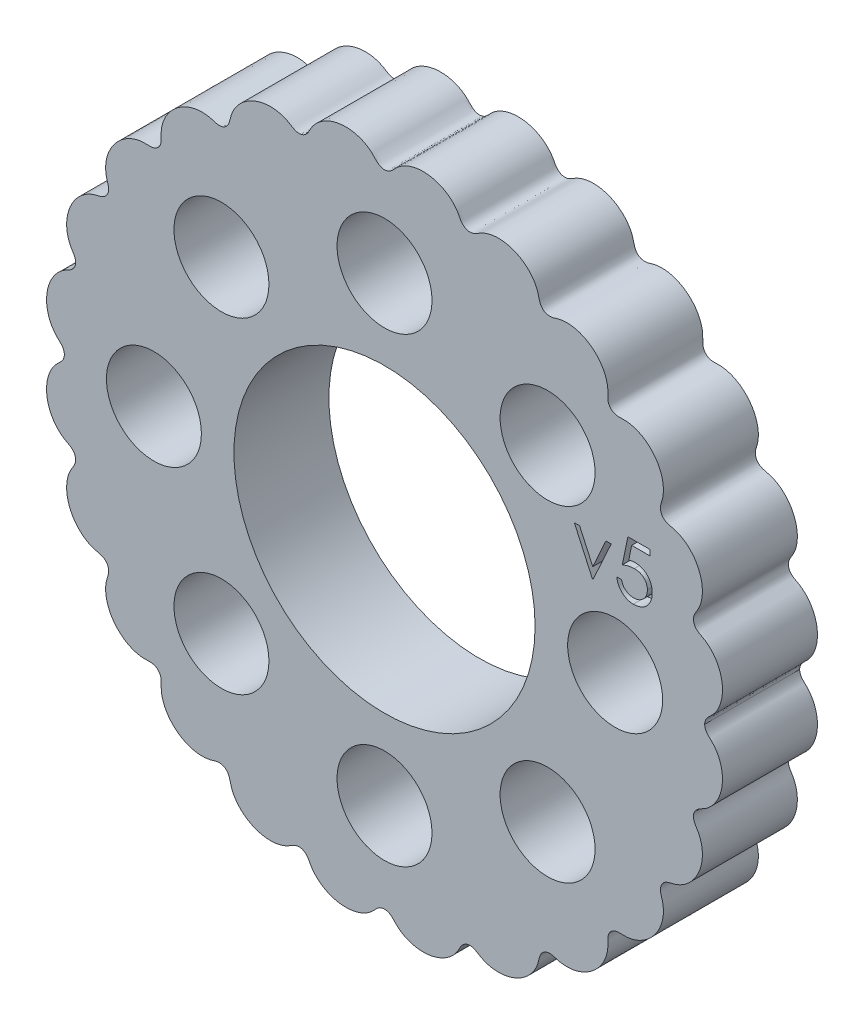
SolidWorks part; units mm, degrees
ref_plane "Plan de face" through (0, 0, 0) normal (0, 0, 1) x (1, 0, 0)
ref_plane "Plan de dessus" through (0, 0, 0) normal (0, 1, 0) x (1, 0, 0)
ref_plane "Plan de droite" through (0, 0, 0) normal (1, 0, 0) x (0, 0, -1)
sketch "Esquisse1" plane through (0, 0, 0) normal (0, 0, 1) x (1, 0, 0)
  line L0 (-1000, 0) -> (49000, 0) construction
  spline S0 degree 4 poles (22.9955, 6.6042) (22.9643, 6.5397) (22.914, 6.4032) (22.9023, 6.1862) (23.0214, 5.9244) (23.2219, 5.7605) (23.4288, 5.659) (23.6594, 5.5306) (23.9059, 5.3649) (24.1666, 5.1353) (24.4254, 4.835) (24.6422, 4.5029) (24.8162, 4.1468) (24.946, 3.7722) (25.0308, 3.385) (25.0698, 2.9906) (25.0624, 2.5943) (25.0079, 2.2017) (24.9068, 1.8224) (24.7781, 1.5066) (24.64, 1.2523) (24.5081, 1.0548) (24.3917, 0.9046) (24.2647, 0.7631) (24.1289, 0.6302) (24.012, 0.5251) (23.9248, 0.4355) (23.8688, 0.3622) (23.8363, 0.3122) (23.8082, 0.2597) (23.7852, 0.2044) (23.7697, 0.1547) (23.76, 0.1121) (23.7533, 0.0661) (23.7501, 0.0228) (23.7495, -0.004) (23.7513, -0.04) (23.7542, -0.0715) (23.7595, -0.1093) (23.7688, -0.1512) (23.7835, -0.1997) (23.8056, -0.2538) (23.8324, -0.3054) (23.8635, -0.3546) (23.9194, -0.4297) (24.009, -0.5227) (24.1313, -0.6322) (24.2737, -0.7721) (24.4392, -0.959) (24.6145, -1.2025) (24.7855, -1.5135) (24.9316, -1.8961) (25.0271, -2.299) (25.0708, -2.7153) (25.0622, -3.1311) (25.0033, -3.5401) (24.8958, -3.9363) (24.7419, -4.314) (24.5445, -4.6645) (24.307, -4.9822) (24.0331, -5.2614) (23.7654, -5.4667) (23.5164, -5.6129) (23.2956, -5.7243) (23.1195, -5.8363) (22.9763, -6.0087) (22.9044, -6.234) (22.925, -6.462) (23.0164, -6.6581) (23.1266, -6.8267) (23.2244, -6.9889) (23.3341, -7.1984) (23.4412, -7.4619) (23.5336, -7.7957) (23.5876, -8.2004) (23.5865, -8.623) (23.5267, -9.0558) (23.3808, -9.5868) (23.1436, -10.0885) (22.8209, -10.5434) (22.4327, -10.9196) (22.1006, -11.1627) (21.7948, -11.3267) (21.5321, -11.4304) (21.3065, -11.4954) (21.1232, -11.5381) (20.9306, -11.5808) (20.7385, -11.6689) (20.5325, -11.8672) (20.4495, -12.16) (20.5219, -12.4298) (20.6167, -12.7241) (20.6818, -13.0067) (20.7176, -13.3406) (20.7046, -13.7295) (20.6405, -14.1156) (20.5273, -14.4945) (20.3673, -14.8595) (20.1602, -15.2112) (19.9061, -15.5428) (19.6059, -15.8469) (19.261, -16.115) (18.8955, -16.3273) (18.5181, -16.4829) (18.1828, -16.5697) (17.9011, -16.6087) (17.6647, -16.6185) (17.4754, -16.6149) (17.2743, -16.6037) (17.0588, -16.6226) (16.851, -16.7187) (16.6918, -16.8937) (16.6141, -17.104) (16.6052, -17.3124) (16.6191, -17.5593) (16.617, -17.8481) (16.5731, -18.1826) (16.4683, -18.5594) (16.3118, -18.9239) (16.107, -19.2701) (15.8569, -19.5923) (15.5674, -19.8834) (15.2427, -20.1389) (14.8869, -20.3543) (14.5046, -20.5246) (14.1078, -20.6433) (13.7035, -20.7081) (13.2985, -20.7166) (12.9508, -20.673) (12.6603, -20.5981) (12.4161, -20.517) (12.2029, -20.4723) (11.9744, -20.5019) (11.768, -20.6211) (11.6281, -20.8042) (11.5602, -21.0112) (11.5084, -21.2632) (11.428, -21.5523) (11.2919, -21.8752) (11.082, -22.2216) (10.8237, -22.5394) (10.5226, -22.8236) (10.1839, -23.0696) (9.8195, -23.2701) (9.4358, -23.4235) (9.039, -23.5286) (8.6349, -23.5841) (8.2327, -23.5884) (7.8388, -23.5416) (7.4601, -23.444) (7.1484, -23.3148) (6.8973, -23.1723) (6.6904, -23.0367) (6.5054, -22.9402) (6.2844, -22.9024) (6.0534, -22.9528) (5.8662, -23.0846) (5.7421, -23.2618) (5.6512, -23.4416) (5.5596, -23.6073) (5.4331, -23.8072) (5.2584, -24.0316) (5.0155, -24.2786) (4.6921, -24.5276) (4.2308, -24.7924) (3.7121, -24.9769) (3.1672, -25.0695) (2.6142, -25.0665) (2.1723, -25.0046) (1.7597, -24.8871) (1.3831, -24.721) (1.0882, -24.5382) (0.867, -24.3625) (0.6979, -24.1997) (0.5693, -24.0623) (0.436, -23.9168) (0.2637, -23.7945) (-0.011, -23.7153) (-0.3061, -23.7898) (-0.5036, -23.9874) (-0.7111, -24.2166) (-0.9232, -24.4143) (-1.1945, -24.6122) (-1.5378, -24.7955) (-1.9042, -24.933) (-2.289, -25.0244) (-2.6851, -25.0684) (-3.0932, -25.0648) (-3.5074, -25.0106) (-3.9209, -24.9026) (-4.3256, -24.738) (-4.6921, -24.5276) (-5.0155, -24.2786) (-5.2584, -24.0316) (-5.4331, -23.8072) (-5.5596, -23.6073) (-5.6512, -23.4416) (-5.7421, -23.2618) (-5.8662, -23.0846) (-6.0534, -22.9528) (-6.2844, -22.9024) (-6.5054, -22.9402) (-6.6904, -23.0367) (-6.8973, -23.1723) (-7.1484, -23.3148) (-7.4601, -23.444) (-7.8388, -23.5416) (-8.2327, -23.5884) (-8.6349, -23.5841) (-9.039, -23.5286) (-9.4358, -23.4235) (-9.8195, -23.2701) (-10.1839, -23.0696) (-10.5226, -22.8236) (-10.8237, -22.5394) (-11.082, -22.2216) (-11.2919, -21.8752) (-11.428, -21.5523) (-11.5084, -21.2632) (-11.5602, -21.0112) (-11.6281, -20.8042) (-11.768, -20.6211) (-11.9744, -20.5019) (-12.2029, -20.4723) (-12.4161, -20.517) (-12.6603, -20.5981) (-12.9508, -20.673) (-13.2985, -20.7166) (-13.7035, -20.7081) (-14.1078, -20.6433) (-14.6048, -20.4946) (-15.1642, -20.2163) (-15.6552, -19.8308) (-16.055, -19.3579) (-16.3118, -18.9239) (-16.4683, -18.5594) (-16.5731, -18.1826) (-16.617, -17.8481) (-16.6191, -17.5593) (-16.6052, -17.3124) (-16.6141, -17.104) (-16.6918, -16.8937) (-16.851, -16.7187) (-17.0588, -16.6226) (-17.2743, -16.6037) (-17.4754, -16.6149) (-17.6647, -16.6185) (-17.9011, -16.6087) (-18.1828, -16.5697) (-18.5181, -16.4829) (-18.8955, -16.3273) (-19.261, -16.1151) (-19.6059, -15.8469) (-19.9061, -15.5428) (-20.1602, -15.2112) (-20.3673, -14.8595) (-20.5273, -14.4945) (-20.6405, -14.1156) (-20.7046, -13.7294) (-20.7175, -13.3407) (-20.6818, -13.0066) (-20.6166, -12.7243) (-20.522, -12.4295) (-20.4494, -12.1605) (-20.5243, -11.8962) (-20.683, -11.7227) (-20.8176, -11.632) (-20.958, -11.5755) (-21.1234, -11.5373) (-21.3064, -11.4958) (-21.5321, -11.4302) (-21.7948, -11.3268) (-22.1006, -11.1626) (-22.4327, -10.9196) (-22.7408, -10.6211) (-23.0153, -10.2693) (-23.2393, -9.8862) (-23.4104, -9.4792) (-23.5267, -9.0558) (-23.5865, -8.623) (-23.5876, -8.2004) (-23.5336, -7.7957) (-23.4412, -7.4619) (-23.3341, -7.1984) (-23.2244, -6.9889) (-23.1266, -6.8267) (-23.0164, -6.6581) (-22.925, -6.462) (-22.9044, -6.234) (-22.9763, -6.0087) (-23.1195, -5.8363) (-23.2956, -5.7243) (-23.5164, -5.6129) (-23.7654, -5.4667) (-24.0331, -5.2614) (-24.307, -4.9822) (-24.5445, -4.6645) (-24.7419, -4.314) (-24.8958, -3.9363) (-25.0033, -3.5401) (-25.0622, -3.1311) (-25.0708, -2.7153) (-25.0271, -2.299) (-24.9316, -1.8961) (-24.7855, -1.5135) (-24.6145, -1.2025) (-24.4393, -0.959) (-24.2737, -0.7721) (-24.1313, -0.6321) (-23.9982, -0.5131) (-23.8995, -0.4084) (-23.8391, -0.3182) (-23.8055, -0.2539) (-23.7835, -0.1997) (-23.7688, -0.1512) (-23.7595, -0.1093) (-23.7542, -0.0715) (-23.7513, -0.04) (-23.7495, -0.0037) (-23.7502, 0.0234) (-23.7534, 0.0677) (-23.7604, 0.1144) (-23.7705, 0.1578) (-23.7867, 0.2087) (-23.8107, 0.2649) (-23.8399, 0.3183) (-23.8736, 0.369) (-23.9317, 0.4432) (-24.0215, 0.5339) (-24.141, 0.6413) (-24.279, 0.7779) (-24.4075, 0.9235) (-24.5249, 1.0783) (-24.6575, 1.2816) (-24.7976, 1.5478) (-24.9275, 1.8824) (-25.0256, 2.2876) (-25.071, 2.7111) (-25.0623, 3.1368) (-25.0002, 3.5582) (-24.8859, 3.9683) (-24.7199, 4.3608) (-24.4999, 4.7349) (-24.2231, 5.0813) (-23.9331, 5.3469) (-23.6469, 5.5411) (-23.3456, 5.7009) (-23.0735, 5.8417) (-22.8982, 6.1368) (-22.9147, 6.4027) (-22.9638, 6.54) (-22.9956, 6.6042) knots 0 0 0 0 0 0.002762 0.005524 0.008057 0.010589 0.012487 0.014385 0.018181 0.021977 0.025773 0.029569 0.033366 0.037162 0.040959 0.044755 0.048552 0.052348 0.056144 0.059791 0.061614 0.063437 0.06526 0.067083 0.068906 0.070729 0.071301 0.071873 0.072445 0.073016 0.073588 0.07416 0.074446 0.074731 0.075303 0.075582 0.075861 0.07614 0.076419 0.076977 0.077535 0.078093 0.078652 0.07921 0.079768 0.081683 0.083599 0.085515 0.08743 0.091261 0.095093 0.099101 0.103109 0.107118 0.111126 0.115032 0.118938 0.122843 0.126749 0.130438 0.134127 0.137815 0.13966 0.141504 0.143638 0.145771 0.148068 0.150364 0.15218 0.153996 0.155812 0.157628 0.16126 0.164892 0.169075 0.173257 0.177439 0.181621 0.190162 0.194433 0.198704 0.20231 0.205917 0.20772 0.209523 0.211327 0.21313 0.215313 0.217496 0.222107 0.223949 0.225791 0.229476 0.23316 0.236844 0.240662 0.24448 0.248298 0.252116 0.256299 0.260481 0.264663 0.268845 0.272477 0.276109 0.277925 0.279741 0.281557 0.283373 0.28567 0.287966 0.2901 0.292233 0.294078 0.295922 0.299611 0.3033 0.306988 0.310894 0.3148 0.318706 0.322612 0.32662 0.330628 0.334637 0.338645 0.342476 0.346307 0.350139 0.352054 0.35397 0.356202 0.358434 0.360667 0.362899 0.364815 0.36673 0.370561 0.374393 0.378224 0.382232 0.386241 0.390249 0.394257 0.398163 0.402069 0.405975 0.40988 0.413569 0.417258 0.420947 0.422791 0.424635 0.426769 0.428902 0.431199 0.433495 0.435311 0.437127 0.438943 0.440759 0.444392 0.448024 0.452206 0.456388 0.464752 0.469023 0.473294 0.477564 0.481835 0.485441 0.489048 0.490851 0.492655 0.494458 0.496261 0.498444 0.500627 0.505239 0.507081 0.508923 0.512607 0.516291 0.519975 0.523793 0.527611 0.53143 0.535248 0.53943 0.543612 0.547794 0.551976 0.555609 0.559241 0.561057 0.562873 0.564689 0.566505 0.568801 0.571098 0.573231 0.575365 0.577209 0.579053 0.582742 0.586431 0.59012 0.594025 0.597931 0.601837 0.605743 0.609751 0.61376 0.617768 0.621776 0.625607 0.629439 0.63327 0.635186 0.637101 0.639333 0.641566 0.643798 0.64603 0.647946 0.649861 0.653693 0.657524 0.661355 0.665364 0.669372 0.677388 0.6852 0.689106 0.693012 0.6967 0.700389 0.704078 0.705922 0.707767 0.7099 0.712034 0.71433 0.716627 0.718443 0.720259 0.722075 0.723891 0.727523 0.731155 0.735337 0.739519 0.743701 0.747884 0.751702 0.75552 0.759338 0.763156 0.76684 0.770525 0.774209 0.776051 0.777893 0.782504 0.784687 0.785779 0.78687 0.788673 0.790477 0.79228 0.794083 0.79769 0.801296 0.805567 0.809838 0.814108 0.818379 0.822561 0.826743 0.830926 0.835108 0.83874 0.842372 0.844188 0.846004 0.84782 0.849636 0.851932 0.854229 0.856362 0.858496 0.86034 0.862185 0.865873 0.869562 0.873251 0.877157 0.881063 0.884968 0.888874 0.892882 0.896891 0.900899 0.904907 0.908739 0.91257 0.914486 0.916401 0.918317 0.920232 0.921349 0.921907 0.922465 0.923023 0.923581 0.92386 0.924139 0.924418 0.924697 0.925281 0.925573 0.925865 0.926449 0.927033 0.927617 0.928201 0.928785 0.929369 0.931232 0.933095 0.934957 0.93682 0.938683 0.940546 0.944272 0.94835 0.952428 0.956506 0.960584 0.964661 0.968739 0.972817 0.976894 0.98129 0.985685 0.987883 0.99008 0.994476 0.997238 1 1 1 1 1 construction
  spline S1 degree 4 poles (23.75, 0) (23.75, -0.0062) (23.7502, -0.0186) (23.7513, -0.04) (23.7542, -0.0715) (23.7595, -0.1093) (23.7688, -0.1512) (23.7835, -0.1997) (23.8056, -0.2538) (23.8324, -0.3054) (23.8635, -0.3546) (23.9194, -0.4297) (24.009, -0.5227) (24.1313, -0.6322) (24.2737, -0.7721) (24.4392, -0.959) (24.6145, -1.2025) (24.7855, -1.5135) (24.9316, -1.8961) (25.0271, -2.299) (25.0708, -2.7153) (25.0622, -3.1311) (25.0033, -3.5401) (24.8958, -3.9363) (24.7419, -4.314) (24.5445, -4.6645) (24.307, -4.9822) (24.0331, -5.2614) (23.7654, -5.4667) (23.5164, -5.6129) (23.2956, -5.7243) (23.1195, -5.8363) (22.9763, -6.0087) (22.9044, -6.234) (22.925, -6.462) (23.0164, -6.6581) (23.1266, -6.8267) (23.2244, -6.9889) (23.3341, -7.1984) (23.4412, -7.4619) (23.5336, -7.7957) (23.5876, -8.2004) (23.5865, -8.623) (23.5267, -9.0558) (23.3808, -9.5868) (23.1436, -10.0885) (22.8209, -10.5434) (22.4327, -10.9196) (22.1006, -11.1627) (21.7948, -11.3267) (21.5321, -11.4304) (21.3065, -11.4954) (21.1232, -11.5381) (20.9306, -11.5808) (20.7385, -11.6689) (20.5325, -11.8672) (20.4495, -12.16) (20.5219, -12.4298) (20.6167, -12.7241) (20.6818, -13.0067) (20.7176, -13.3406) (20.7046, -13.7295) (20.6405, -14.1156) (20.5273, -14.4945) (20.3673, -14.8595) (20.1602, -15.2112) (19.9061, -15.5428) (19.6059, -15.8469) (19.261, -16.115) (18.8955, -16.3273) (18.5181, -16.4829) (18.1828, -16.5697) (17.9011, -16.6087) (17.6647, -16.6185) (17.4754, -16.6149) (17.2743, -16.6037) (17.0588, -16.6226) (16.851, -16.7187) (16.6918, -16.8937) (16.6141, -17.104) (16.6052, -17.3124) (16.6191, -17.5593) (16.617, -17.8481) (16.5731, -18.1826) (16.4683, -18.5594) (16.3118, -18.9239) (16.107, -19.2701) (15.8569, -19.5923) (15.5674, -19.8834) (15.2427, -20.1389) (14.8869, -20.3543) (14.5046, -20.5246) (14.1078, -20.6433) (13.7035, -20.7081) (13.2985, -20.7166) (12.9508, -20.673) (12.6603, -20.5981) (12.4161, -20.517) (12.2029, -20.4723) (11.9744, -20.5019) (11.768, -20.6211) (11.6281, -20.8042) (11.5602, -21.0112) (11.5084, -21.2632) (11.428, -21.5523) (11.2919, -21.8752) (11.082, -22.2216) (10.8237, -22.5394) (10.5226, -22.8236) (10.1839, -23.0696) (9.8195, -23.2701) (9.4358, -23.4235) (9.039, -23.5286) (8.6349, -23.5841) (8.2327, -23.5884) (7.8388, -23.5416) (7.4601, -23.444) (7.1484, -23.3148) (6.8973, -23.1723) (6.6904, -23.0367) (6.5054, -22.9402) (6.2844, -22.9024) (6.0534, -22.9528) (5.8662, -23.0846) (5.7421, -23.2618) (5.6512, -23.4416) (5.5596, -23.6073) (5.4331, -23.8072) (5.2584, -24.0316) (5.0155, -24.2786) (4.6921, -24.5276) (4.2308, -24.7924) (3.7121, -24.9769) (3.1672, -25.0695) (2.6142, -25.0665) (2.1723, -25.0046) (1.7597, -24.8871) (1.3831, -24.721) (1.0882, -24.5382) (0.867, -24.3625) (0.6979, -24.1997) (0.5693, -24.0623) (0.436, -23.9168) (0.2637, -23.7945) (-0.011, -23.7153) (-0.3061, -23.7898) (-0.5036, -23.9874) (-0.7111, -24.2166) (-0.9232, -24.4143) (-1.1945, -24.6122) (-1.5378, -24.7955) (-1.9042, -24.933) (-2.289, -25.0244) (-2.6851, -25.0684) (-3.0932, -25.0648) (-3.5074, -25.0106) (-3.9209, -24.9026) (-4.3256, -24.738) (-4.6921, -24.5276) (-5.0155, -24.2786) (-5.2584, -24.0316) (-5.4331, -23.8072) (-5.5596, -23.6073) (-5.6512, -23.4416) (-5.7421, -23.2618) (-5.8662, -23.0846) (-6.0534, -22.9528) (-6.2844, -22.9024) (-6.5054, -22.9402) (-6.6904, -23.0367) (-6.8973, -23.1723) (-7.1484, -23.3148) (-7.4601, -23.444) (-7.8388, -23.5416) (-8.2327, -23.5884) (-8.6349, -23.5841) (-9.039, -23.5286) (-9.4358, -23.4235) (-9.8195, -23.2701) (-10.1839, -23.0696) (-10.5226, -22.8236) (-10.8237, -22.5394) (-11.082, -22.2216) (-11.2919, -21.8752) (-11.428, -21.5523) (-11.5084, -21.2632) (-11.5602, -21.0112) (-11.6281, -20.8042) (-11.768, -20.6211) (-11.9744, -20.5019) (-12.2029, -20.4723) (-12.4161, -20.517) (-12.6603, -20.5981) (-12.9508, -20.673) (-13.2985, -20.7166) (-13.7035, -20.7081) (-14.1078, -20.6433) (-14.6048, -20.4946) (-15.1642, -20.2163) (-15.6552, -19.8308) (-16.055, -19.3579) (-16.3118, -18.9239) (-16.4683, -18.5594) (-16.5731, -18.1826) (-16.617, -17.8481) (-16.6191, -17.5593) (-16.6052, -17.3124) (-16.6141, -17.104) (-16.6918, -16.8937) (-16.851, -16.7187) (-17.0588, -16.6226) (-17.2743, -16.6037) (-17.4754, -16.6149) (-17.6647, -16.6185) (-17.9011, -16.6087) (-18.1828, -16.5697) (-18.5181, -16.4829) (-18.8955, -16.3273) (-19.261, -16.1151) (-19.6059, -15.8469) (-19.9061, -15.5428) (-20.1602, -15.2112) (-20.3673, -14.8595) (-20.5273, -14.4945) (-20.6405, -14.1156) (-20.7046, -13.7294) (-20.7175, -13.3407) (-20.6818, -13.0066) (-20.6166, -12.7243) (-20.522, -12.4295) (-20.4494, -12.1605) (-20.5243, -11.8962) (-20.683, -11.7227) (-20.8176, -11.632) (-20.958, -11.5755) (-21.1234, -11.5373) (-21.3064, -11.4958) (-21.5321, -11.4302) (-21.7948, -11.3268) (-22.1006, -11.1626) (-22.4327, -10.9196) (-22.7408, -10.6211) (-23.0153, -10.2693) (-23.2393, -9.8862) (-23.4104, -9.4792) (-23.5267, -9.0558) (-23.5865, -8.623) (-23.5876, -8.2004) (-23.5336, -7.7957) (-23.4412, -7.4619) (-23.3341, -7.1984) (-23.2244, -6.9889) (-23.1266, -6.8267) (-23.0164, -6.6581) (-22.925, -6.462) (-22.9044, -6.234) (-22.9763, -6.0087) (-23.1195, -5.8363) (-23.2956, -5.7243) (-23.5164, -5.6129) (-23.7654, -5.4667) (-24.0331, -5.2614) (-24.307, -4.9822) (-24.5445, -4.6645) (-24.7419, -4.314) (-24.8958, -3.9363) (-25.0033, -3.5401) (-25.0622, -3.1311) (-25.0708, -2.7153) (-25.0271, -2.299) (-24.9316, -1.8961) (-24.7855, -1.5135) (-24.6145, -1.2025) (-24.4393, -0.959) (-24.2737, -0.7721) (-24.1313, -0.6321) (-23.9982, -0.5131) (-23.8995, -0.4084) (-23.8391, -0.3182) (-23.8055, -0.2539) (-23.7835, -0.1997) (-23.7688, -0.1512) (-23.7595, -0.1093) (-23.7542, -0.0715) (-23.7513, -0.04) (-23.7502, -0.0186) (-23.75, -0.0062) (-23.75, 0) knots 0.075303 0.075303 0.075303 0.075303 0.075303 0.075582 0.075861 0.07614 0.076419 0.076977 0.077535 0.078093 0.078652 0.07921 0.079768 0.081683 0.083599 0.085515 0.08743 0.091261 0.095093 0.099101 0.103109 0.107118 0.111126 0.115032 0.118938 0.122843 0.126749 0.130438 0.134127 0.137815 0.13966 0.141504 0.143638 0.145771 0.148068 0.150364 0.15218 0.153996 0.155812 0.157628 0.16126 0.164892 0.169075 0.173257 0.177439 0.181621 0.190162 0.194433 0.198704 0.20231 0.205917 0.20772 0.209523 0.211327 0.21313 0.215313 0.217496 0.222107 0.223949 0.225791 0.229476 0.23316 0.236844 0.240662 0.24448 0.248298 0.252116 0.256299 0.260481 0.264663 0.268845 0.272477 0.276109 0.277925 0.279741 0.281557 0.283373 0.28567 0.287966 0.2901 0.292233 0.294078 0.295922 0.299611 0.3033 0.306988 0.310894 0.3148 0.318706 0.322612 0.32662 0.330628 0.334637 0.338645 0.342476 0.346307 0.350139 0.352054 0.35397 0.356202 0.358434 0.360667 0.362899 0.364815 0.36673 0.370561 0.374393 0.378224 0.382232 0.386241 0.390249 0.394257 0.398163 0.402069 0.405975 0.40988 0.413569 0.417258 0.420947 0.422791 0.424635 0.426769 0.428902 0.431199 0.433495 0.435311 0.437127 0.438943 0.440759 0.444392 0.448024 0.452206 0.456388 0.464752 0.469023 0.473294 0.477564 0.481835 0.485441 0.489048 0.490851 0.492655 0.494458 0.496261 0.498444 0.500627 0.505239 0.507081 0.508923 0.512607 0.516291 0.519975 0.523793 0.527611 0.53143 0.535248 0.53943 0.543612 0.547794 0.551976 0.555609 0.559241 0.561057 0.562873 0.564689 0.566505 0.568801 0.571098 0.573231 0.575365 0.577209 0.579053 0.582742 0.586431 0.59012 0.594025 0.597931 0.601837 0.605743 0.609751 0.61376 0.617768 0.621776 0.625607 0.629439 0.63327 0.635186 0.637101 0.639333 0.641566 0.643798 0.64603 0.647946 0.649861 0.653693 0.657524 0.661355 0.665364 0.669372 0.677388 0.6852 0.689106 0.693012 0.6967 0.700389 0.704078 0.705922 0.707767 0.7099 0.712034 0.71433 0.716627 0.718443 0.720259 0.722075 0.723891 0.727523 0.731155 0.735337 0.739519 0.743701 0.747884 0.751702 0.75552 0.759338 0.763156 0.76684 0.770525 0.774209 0.776051 0.777893 0.782504 0.784687 0.785779 0.78687 0.788673 0.790477 0.79228 0.794083 0.79769 0.801296 0.805567 0.809838 0.814108 0.818379 0.822561 0.826743 0.830926 0.835108 0.83874 0.842372 0.844188 0.846004 0.84782 0.849636 0.851932 0.854229 0.856362 0.858496 0.86034 0.862185 0.865873 0.869562 0.873251 0.877157 0.881063 0.884968 0.888874 0.892882 0.896891 0.900899 0.904907 0.908739 0.91257 0.914486 0.916401 0.918317 0.920232 0.921349 0.921907 0.922465 0.923023 0.923581 0.92386 0.924139 0.924418 0.924697 0.924697 0.924697 0.924697 0.924697 construction
  spline S2 degree 4 poles (23.75, 0) (23.75, 0.0062) (23.7502, 0.0186) (23.7513, 0.04) (23.7542, 0.0715) (23.7595, 0.1093) (23.7688, 0.1512) (23.7835, 0.1997) (23.8056, 0.2538) (23.8324, 0.3054) (23.8635, 0.3546) (23.9194, 0.4297) (24.009, 0.5227) (24.1313, 0.6322) (24.2737, 0.7721) (24.4392, 0.959) (24.6145, 1.2025) (24.7855, 1.5135) (24.9316, 1.8961) (25.0271, 2.299) (25.0708, 2.7153) (25.0622, 3.1311) (25.0033, 3.5401) (24.8958, 3.9363) (24.7419, 4.314) (24.5445, 4.6645) (24.307, 4.9822) (24.0331, 5.2614) (23.7654, 5.4667) (23.5164, 5.6129) (23.2956, 5.7243) (23.1195, 5.8363) (22.9763, 6.0087) (22.9044, 6.234) (22.925, 6.462) (23.0164, 6.6581) (23.1266, 6.8267) (23.2244, 6.9889) (23.3341, 7.1984) (23.4412, 7.4619) (23.5336, 7.7957) (23.5876, 8.2004) (23.5865, 8.623) (23.5267, 9.0558) (23.3808, 9.5868) (23.1436, 10.0885) (22.8209, 10.5434) (22.4327, 10.9196) (22.1006, 11.1627) (21.7948, 11.3267) (21.5321, 11.4304) (21.3065, 11.4954) (21.1232, 11.5381) (20.9306, 11.5808) (20.7385, 11.6689) (20.5325, 11.8672) (20.4495, 12.16) (20.5219, 12.4298) (20.6167, 12.7241) (20.6818, 13.0067) (20.7176, 13.3406) (20.7046, 13.7295) (20.6405, 14.1156) (20.5273, 14.4945) (20.3673, 14.8595) (20.1602, 15.2112) (19.9061, 15.5428) (19.6059, 15.8469) (19.261, 16.115) (18.8955, 16.3273) (18.5181, 16.4829) (18.1828, 16.5697) (17.9011, 16.6087) (17.6647, 16.6185) (17.4754, 16.6149) (17.2743, 16.6037) (17.0588, 16.6226) (16.851, 16.7187) (16.6918, 16.8937) (16.6141, 17.104) (16.6052, 17.3124) (16.6191, 17.5593) (16.617, 17.8481) (16.5731, 18.1826) (16.4683, 18.5594) (16.3118, 18.9239) (16.107, 19.2701) (15.8569, 19.5923) (15.5674, 19.8834) (15.2427, 20.1389) (14.8869, 20.3543) (14.5046, 20.5246) (14.1078, 20.6433) (13.7035, 20.7081) (13.2985, 20.7166) (12.9508, 20.673) (12.6603, 20.5981) (12.4161, 20.517) (12.2029, 20.4723) (11.9744, 20.5019) (11.768, 20.6211) (11.6281, 20.8042) (11.5602, 21.0112) (11.5084, 21.2632) (11.428, 21.5523) (11.2919, 21.8752) (11.082, 22.2216) (10.8237, 22.5394) (10.5226, 22.8236) (10.1839, 23.0696) (9.8195, 23.2701) (9.4358, 23.4235) (9.039, 23.5286) (8.6349, 23.5841) (8.2327, 23.5884) (7.8388, 23.5416) (7.4601, 23.444) (7.1484, 23.3148) (6.8973, 23.1723) (6.6904, 23.0367) (6.5054, 22.9402) (6.2844, 22.9024) (6.0534, 22.9528) (5.8662, 23.0846) (5.7421, 23.2618) (5.6512, 23.4416) (5.5596, 23.6073) (5.4331, 23.8072) (5.2584, 24.0316) (5.0155, 24.2786) (4.6921, 24.5276) (4.2308, 24.7924) (3.7121, 24.9769) (3.1672, 25.0695) (2.6142, 25.0665) (2.1723, 25.0046) (1.7597, 24.8871) (1.3831, 24.721) (1.0882, 24.5382) (0.867, 24.3625) (0.6979, 24.1997) (0.5693, 24.0623) (0.436, 23.9168) (0.2637, 23.7945) (-0.011, 23.7153) (-0.3061, 23.7898) (-0.5036, 23.9874) (-0.7111, 24.2166) (-0.9232, 24.4143) (-1.1945, 24.6122) (-1.5378, 24.7955) (-1.9042, 24.933) (-2.289, 25.0244) (-2.6851, 25.0684) (-3.0932, 25.0648) (-3.5074, 25.0106) (-3.9209, 24.9026) (-4.3256, 24.738) (-4.6921, 24.5276) (-5.0155, 24.2786) (-5.2584, 24.0316) (-5.4331, 23.8072) (-5.5596, 23.6073) (-5.6512, 23.4416) (-5.7421, 23.2618) (-5.8662, 23.0846) (-6.0534, 22.9528) (-6.2844, 22.9024) (-6.5054, 22.9402) (-6.6904, 23.0367) (-6.8973, 23.1723) (-7.1484, 23.3148) (-7.4601, 23.444) (-7.8388, 23.5416) (-8.2327, 23.5884) (-8.6349, 23.5841) (-9.039, 23.5286) (-9.4358, 23.4235) (-9.8195, 23.2701) (-10.1839, 23.0696) (-10.5226, 22.8236) (-10.8237, 22.5394) (-11.082, 22.2216) (-11.2919, 21.8752) (-11.428, 21.5523) (-11.5084, 21.2632) (-11.5602, 21.0112) (-11.6281, 20.8042) (-11.768, 20.6211) (-11.9744, 20.5019) (-12.2029, 20.4723) (-12.4161, 20.517) (-12.6603, 20.5981) (-12.9508, 20.673) (-13.2985, 20.7166) (-13.7035, 20.7081) (-14.1078, 20.6433) (-14.6048, 20.4946) (-15.1642, 20.2163) (-15.6552, 19.8308) (-16.055, 19.3579) (-16.3118, 18.9239) (-16.4683, 18.5594) (-16.5731, 18.1826) (-16.617, 17.8481) (-16.6191, 17.5593) (-16.6052, 17.3124) (-16.6141, 17.104) (-16.6918, 16.8937) (-16.851, 16.7187) (-17.0588, 16.6226) (-17.2743, 16.6037) (-17.4754, 16.6149) (-17.6647, 16.6185) (-17.9011, 16.6087) (-18.1828, 16.5697) (-18.5181, 16.4829) (-18.8955, 16.3273) (-19.261, 16.1151) (-19.6059, 15.8469) (-19.9061, 15.5428) (-20.1602, 15.2112) (-20.3673, 14.8595) (-20.5273, 14.4945) (-20.6405, 14.1156) (-20.7046, 13.7294) (-20.7175, 13.3407) (-20.6818, 13.0066) (-20.6166, 12.7243) (-20.522, 12.4295) (-20.4494, 12.1605) (-20.5243, 11.8962) (-20.683, 11.7227) (-20.8176, 11.632) (-20.958, 11.5755) (-21.1234, 11.5373) (-21.3064, 11.4958) (-21.5321, 11.4302) (-21.7948, 11.3268) (-22.1006, 11.1626) (-22.4327, 10.9196) (-22.7408, 10.6211) (-23.0153, 10.2693) (-23.2393, 9.8862) (-23.4104, 9.4792) (-23.5267, 9.0558) (-23.5865, 8.623) (-23.5876, 8.2004) (-23.5336, 7.7957) (-23.4412, 7.4619) (-23.3341, 7.1984) (-23.2244, 6.9889) (-23.1266, 6.8267) (-23.0164, 6.6581) (-22.925, 6.462) (-22.9044, 6.234) (-22.9763, 6.0087) (-23.1195, 5.8363) (-23.2956, 5.7243) (-23.5164, 5.6129) (-23.7654, 5.4667) (-24.0331, 5.2614) (-24.307, 4.9822) (-24.5445, 4.6645) (-24.7419, 4.314) (-24.8958, 3.9363) (-25.0033, 3.5401) (-25.0622, 3.1311) (-25.0708, 2.7153) (-25.0271, 2.299) (-24.9316, 1.8961) (-24.7855, 1.5135) (-24.6145, 1.2025) (-24.4393, 0.959) (-24.2737, 0.7721) (-24.1313, 0.6321) (-23.9982, 0.5131) (-23.8995, 0.4084) (-23.8391, 0.3182) (-23.8055, 0.2539) (-23.7835, 0.1997) (-23.7688, 0.1512) (-23.7595, 0.1093) (-23.7542, 0.0715) (-23.7513, 0.04) (-23.7502, 0.0186) (-23.75, 0.0062) (-23.75, 0) knots 0.075303 0.075303 0.075303 0.075303 0.075303 0.075582 0.075861 0.07614 0.076419 0.076977 0.077535 0.078093 0.078652 0.07921 0.079768 0.081683 0.083599 0.085515 0.08743 0.091261 0.095093 0.099101 0.103109 0.107118 0.111126 0.115032 0.118938 0.122843 0.126749 0.130438 0.134127 0.137815 0.13966 0.141504 0.143638 0.145771 0.148068 0.150364 0.15218 0.153996 0.155812 0.157628 0.16126 0.164892 0.169075 0.173257 0.177439 0.181621 0.190162 0.194433 0.198704 0.20231 0.205917 0.20772 0.209523 0.211327 0.21313 0.215313 0.217496 0.222107 0.223949 0.225791 0.229476 0.23316 0.236844 0.240662 0.24448 0.248298 0.252116 0.256299 0.260481 0.264663 0.268845 0.272477 0.276109 0.277925 0.279741 0.281557 0.283373 0.28567 0.287966 0.2901 0.292233 0.294078 0.295922 0.299611 0.3033 0.306988 0.310894 0.3148 0.318706 0.322612 0.32662 0.330628 0.334637 0.338645 0.342476 0.346307 0.350139 0.352054 0.35397 0.356202 0.358434 0.360667 0.362899 0.364815 0.36673 0.370561 0.374393 0.378224 0.382232 0.386241 0.390249 0.394257 0.398163 0.402069 0.405975 0.40988 0.413569 0.417258 0.420947 0.422791 0.424635 0.426769 0.428902 0.431199 0.433495 0.435311 0.437127 0.438943 0.440759 0.444392 0.448024 0.452206 0.456388 0.464752 0.469023 0.473294 0.477564 0.481835 0.485441 0.489048 0.490851 0.492655 0.494458 0.496261 0.498444 0.500627 0.505239 0.507081 0.508923 0.512607 0.516291 0.519975 0.523793 0.527611 0.53143 0.535248 0.53943 0.543612 0.547794 0.551976 0.555609 0.559241 0.561057 0.562873 0.564689 0.566505 0.568801 0.571098 0.573231 0.575365 0.577209 0.579053 0.582742 0.586431 0.59012 0.594025 0.597931 0.601837 0.605743 0.609751 0.61376 0.617768 0.621776 0.625607 0.629439 0.63327 0.635186 0.637101 0.639333 0.641566 0.643798 0.64603 0.647946 0.649861 0.653693 0.657524 0.661355 0.665364 0.669372 0.677388 0.6852 0.689106 0.693012 0.6967 0.700389 0.704078 0.705922 0.707767 0.7099 0.712034 0.71433 0.716627 0.718443 0.720259 0.722075 0.723891 0.727523 0.731155 0.735337 0.739519 0.743701 0.747884 0.751702 0.75552 0.759338 0.763156 0.76684 0.770525 0.774209 0.776051 0.777893 0.782504 0.784687 0.785779 0.78687 0.788673 0.790477 0.79228 0.794083 0.79769 0.801296 0.805567 0.809838 0.814108 0.818379 0.822561 0.826743 0.830926 0.835108 0.83874 0.842372 0.844188 0.846004 0.84782 0.849636 0.851932 0.854229 0.856362 0.858496 0.86034 0.862185 0.865873 0.869562 0.873251 0.877157 0.881063 0.884968 0.888874 0.892882 0.896891 0.900899 0.904907 0.908739 0.91257 0.914486 0.916401 0.918317 0.920232 0.921349 0.921907 0.922465 0.923023 0.923581 0.92386 0.924139 0.924418 0.924697 0.924697 0.924697 0.924697 0.924697 construction
  spline S3 degree 1 poles (23.6, 0) (-23.6, 0) knots 0 0 1 1 construction
  spline S4 degree 1 poles (23.6, 0) (-23.6, 0) knots 0 0 1 1 construction
  spline S5 degree 3 poles (23.6, 0) (23.6, 0.1413) (23.695, 0.4365) (23.9841, 0.7) (24.2141, 0.9221) (24.4859, 1.2659) (24.7382, 1.7532) (24.9028, 2.3953) (24.9291, 3.0585) (24.8201, 3.7136) (24.5796, 4.3319) (24.2145, 4.8837) (23.8098, 5.2567) (23.4446, 5.4862) (23.1218, 5.6322) (22.8058, 5.9504) (22.7343, 6.405) (22.9149, 6.792) (23.1004, 7.0616) (23.2413, 7.3578) (23.3797, 7.7712) (23.4552, 8.3172) (23.4005, 8.9778) (23.2102, 9.614) (22.8949, 10.1984) (22.4664, 10.7042) (22.027, 11.0368) (21.6368, 11.2314) (21.3278, 11.341) (21.0066, 11.4006) (20.6047, 11.5464) (20.3336, 11.9192) (20.3321, 12.366) (20.4572, 12.6992) (20.5531, 13.1186) (20.5755, 13.6691) (20.4435, 14.3172) (20.1764, 14.9246) (19.7902, 15.4648) (19.3027, 15.9152) (18.7322, 16.2529) (18.2093, 16.419) (17.7739, 16.4699) (17.4549, 16.4641) (17.0624, 16.4473) (16.6542, 16.6542) (16.4474, 17.0623) (16.464, 17.4549) (16.47, 17.7738) (16.419, 18.2094) (16.2529, 18.7322) (15.9152, 19.3027) (15.4649, 19.7902) (14.9246, 20.1764) (14.3173, 20.4435) (13.669, 20.5755) (13.119, 20.5531) (12.6986, 20.4572) (12.367, 20.3322) (11.9185, 20.3338) (11.5466, 20.6046) (11.4006, 21.0058) (11.3413, 21.3277) (11.2312, 21.6369) (11.0369, 22.0269) (10.7042, 22.4665) (10.1983, 22.8949) (9.614, 23.2102) (8.9778, 23.4005) (8.3172, 23.4552) (7.7711, 23.3797) (7.3579, 23.2413) (7.0615, 23.1004) (6.7919, 22.9149) (6.4049, 22.7343) (5.9505, 22.8058) (5.6322, 23.1217) (5.4863, 23.4443) (5.2567, 23.81) (4.8837, 24.2144) (4.3318, 24.5796) (3.7136, 24.8201) (3.0585, 24.9291) (2.3953, 24.9028) (1.7531, 24.7382) (1.2659, 24.4859) (0.9221, 24.2142) (0.7002, 23.9842) (0.4345, 23.6948) (0.0001, 23.5526) (-0.4343, 23.6948) (-0.7014, 23.9846) (-0.9213, 24.2137) (-1.2665, 24.4862) (-1.753, 24.7381) (-2.3954, 24.9028) (-3.0585, 24.9291) (-3.7136, 24.8201) (-4.3319, 24.5796) (-4.8837, 24.2144) (-5.2567, 23.81) (-5.4863, 23.4443) (-5.6322, 23.1217) (-5.9505, 22.8058) (-6.4049, 22.7343) (-6.7919, 22.9149) (-7.0615, 23.1004) (-7.3579, 23.2413) (-7.7711, 23.3797) (-8.3172, 23.4552) (-8.9778, 23.4005) (-9.614, 23.2102) (-10.1983, 22.8949) (-10.7042, 22.4665) (-11.0369, 22.0269) (-11.2312, 21.6369) (-11.3413, 21.3277) (-11.4006, 21.0058) (-11.5466, 20.6046) (-11.9185, 20.3338) (-12.367, 20.3322) (-12.6986, 20.4572) (-13.119, 20.5531) (-13.669, 20.5755) (-14.3173, 20.4435) (-14.9246, 20.1764) (-15.4649, 19.7902) (-15.9152, 19.3027) (-16.2529, 18.7322) (-16.419, 18.2094) (-16.47, 17.7738) (-16.464, 17.4549) (-16.4474, 17.0623) (-16.6542, 16.6542) (-17.0624, 16.4473) (-17.4549, 16.4641) (-17.7739, 16.4699) (-18.2093, 16.419) (-18.7322, 16.2529) (-19.3027, 15.9152) (-19.7902, 15.4648) (-20.1764, 14.9246) (-20.4435, 14.3172) (-20.5755, 13.6691) (-20.5531, 13.1187) (-20.4572, 12.6991) (-20.3321, 12.3662) (-20.3337, 11.919) (-20.6044, 11.5468) (-21.0061, 11.4007) (-21.3278, 11.3412) (-21.6369, 11.2312) (-22.0269, 11.0369) (-22.4664, 10.7042) (-22.8949, 10.1984) (-23.2102, 9.614) (-23.4005, 8.9778) (-23.4552, 8.3172) (-23.3797, 7.7712) (-23.2413, 7.3578) (-23.1004, 7.0616) (-22.9149, 6.792) (-22.7343, 6.405) (-22.8058, 5.9504) (-23.1218, 5.6322) (-23.4446, 5.4862) (-23.8098, 5.2567) (-24.2145, 4.8837) (-24.5796, 4.3319) (-24.8201, 3.7136) (-24.9291, 3.0585) (-24.9028, 2.3953) (-24.7382, 1.7531) (-24.4859, 1.2659) (-24.2141, 0.9221) (-23.9842, 0.7001) (-23.6948, 0.4363) (-23.6, 0.1412) (-23.6, 0) knots 0.075303 0.075303 0.075303 0.075303 0.078621 0.081939 0.085257 0.088575 0.095211 0.101847 0.108483 0.115118 0.121754 0.12839 0.135026 0.138344 0.141662 0.14498 0.148298 0.151616 0.154934 0.158252 0.16157 0.168206 0.174841 0.181477 0.188113 0.194749 0.201385 0.204703 0.208021 0.211339 0.214657 0.217975 0.221293 0.224611 0.227929 0.234564 0.2412 0.247836 0.254472 0.261108 0.267744 0.27438 0.277698 0.281016 0.284334 0.287652 0.29097 0.294287 0.297605 0.300923 0.307559 0.314195 0.320831 0.327467 0.334103 0.340739 0.347375 0.350693 0.35401 0.357328 0.360646 0.363964 0.367282 0.3706 0.373918 0.380554 0.38719 0.393826 0.400462 0.407098 0.413733 0.417051 0.420369 0.423687 0.427005 0.430323 0.433641 0.436959 0.440277 0.446913 0.453549 0.460185 0.466821 0.473456 0.480092 0.486728 0.490046 0.493364 0.496682 0.5 0.503318 0.506636 0.509954 0.513272 0.519908 0.526544 0.533179 0.539815 0.546451 0.553087 0.559723 0.563041 0.566359 0.569677 0.572995 0.576313 0.579631 0.582949 0.586267 0.592902 0.599538 0.606174 0.61281 0.619446 0.626082 0.6294 0.632718 0.636036 0.639354 0.642672 0.64599 0.649308 0.652625 0.659261 0.665897 0.672533 0.679169 0.685805 0.692441 0.699077 0.702395 0.705713 0.709031 0.712348 0.715666 0.718984 0.722302 0.72562 0.732256 0.738892 0.745528 0.752164 0.7588 0.765436 0.772071 0.775389 0.778707 0.782025 0.785343 0.788661 0.791979 0.795297 0.798615 0.805251 0.811887 0.818523 0.825159 0.831794 0.83843 0.841748 0.845066 0.848384 0.851702 0.85502 0.858338 0.861656 0.864974 0.87161 0.878246 0.884882 0.891518 0.898153 0.904789 0.911425 0.914743 0.918061 0.921379 0.924697 0.924697 0.924697 0.924697
  spline S6 degree 3 poles (-23.6, 0) (-23.6, -0.1412) (-23.6948, -0.4363) (-23.9842, -0.7001) (-24.2141, -0.9221) (-24.4859, -1.2659) (-24.7382, -1.7531) (-24.9028, -2.3953) (-24.9291, -3.0585) (-24.8201, -3.7136) (-24.5796, -4.3319) (-24.2145, -4.8837) (-23.8098, -5.2567) (-23.4446, -5.4862) (-23.1218, -5.6322) (-22.8058, -5.9504) (-22.7343, -6.405) (-22.9149, -6.792) (-23.1004, -7.0616) (-23.2413, -7.3578) (-23.3797, -7.7712) (-23.4552, -8.3172) (-23.4005, -8.9778) (-23.2102, -9.614) (-22.8949, -10.1984) (-22.4664, -10.7042) (-22.0269, -11.0369) (-21.6369, -11.2312) (-21.3278, -11.3412) (-21.0061, -11.4007) (-20.6044, -11.5468) (-20.3337, -11.919) (-20.3321, -12.3662) (-20.4572, -12.6991) (-20.5531, -13.1187) (-20.5755, -13.6691) (-20.4435, -14.3172) (-20.1764, -14.9246) (-19.7902, -15.4648) (-19.3027, -15.9152) (-18.7322, -16.2529) (-18.2093, -16.419) (-17.7739, -16.4699) (-17.4549, -16.4641) (-17.0624, -16.4473) (-16.6542, -16.6542) (-16.4474, -17.0623) (-16.464, -17.4549) (-16.47, -17.7738) (-16.419, -18.2094) (-16.2529, -18.7322) (-15.9152, -19.3027) (-15.4649, -19.7902) (-14.9246, -20.1764) (-14.3173, -20.4435) (-13.669, -20.5755) (-13.119, -20.5531) (-12.6986, -20.4572) (-12.367, -20.3322) (-11.9185, -20.3338) (-11.5466, -20.6046) (-11.4006, -21.0058) (-11.3413, -21.3277) (-11.2312, -21.6369) (-11.0369, -22.0269) (-10.7042, -22.4665) (-10.1983, -22.8949) (-9.614, -23.2102) (-8.9778, -23.4005) (-8.3172, -23.4552) (-7.7711, -23.3797) (-7.3579, -23.2413) (-7.0615, -23.1004) (-6.7919, -22.9149) (-6.4049, -22.7343) (-5.9505, -22.8058) (-5.6322, -23.1217) (-5.4863, -23.4443) (-5.2567, -23.81) (-4.8837, -24.2144) (-4.3319, -24.5796) (-3.7136, -24.8201) (-3.0585, -24.9291) (-2.3954, -24.9028) (-1.753, -24.7381) (-1.2665, -24.4862) (-0.9213, -24.2137) (-0.7014, -23.9846) (-0.4343, -23.6948) (0.0001, -23.5526) (0.4345, -23.6948) (0.7002, -23.9842) (0.9221, -24.2142) (1.2659, -24.4859) (1.7531, -24.7382) (2.3953, -24.9028) (3.0585, -24.9291) (3.7136, -24.8201) (4.3318, -24.5796) (4.8837, -24.2144) (5.2567, -23.81) (5.4863, -23.4443) (5.6322, -23.1217) (5.9505, -22.8058) (6.4049, -22.7343) (6.7919, -22.9149) (7.0615, -23.1004) (7.3579, -23.2413) (7.7711, -23.3797) (8.3172, -23.4552) (8.9778, -23.4005) (9.614, -23.2102) (10.1983, -22.8949) (10.7042, -22.4665) (11.0369, -22.0269) (11.2312, -21.6369) (11.3413, -21.3277) (11.4006, -21.0058) (11.5466, -20.6046) (11.9185, -20.3338) (12.367, -20.3322) (12.6986, -20.4572) (13.119, -20.5531) (13.669, -20.5755) (14.3173, -20.4435) (14.9246, -20.1764) (15.4649, -19.7902) (15.9152, -19.3027) (16.2529, -18.7322) (16.419, -18.2094) (16.47, -17.7738) (16.464, -17.4549) (16.4474, -17.0623) (16.6542, -16.6542) (17.0624, -16.4473) (17.4549, -16.4641) (17.7739, -16.4699) (18.2093, -16.419) (18.7322, -16.2529) (19.3027, -15.9152) (19.7902, -15.4648) (20.1764, -14.9246) (20.4435, -14.3172) (20.5755, -13.6691) (20.5531, -13.1186) (20.4572, -12.6992) (20.3321, -12.366) (20.3336, -11.9192) (20.6047, -11.5464) (21.0066, -11.4006) (21.3278, -11.341) (21.6368, -11.2314) (22.027, -11.0368) (22.4664, -10.7042) (22.8949, -10.1984) (23.2102, -9.614) (23.4005, -8.9778) (23.4552, -8.3172) (23.3797, -7.7712) (23.2413, -7.3578) (23.1004, -7.0616) (22.9149, -6.792) (22.7343, -6.405) (22.8058, -5.9504) (23.1218, -5.6322) (23.4446, -5.4862) (23.8098, -5.2567) (24.2145, -4.8837) (24.5796, -4.3319) (24.8201, -3.7136) (24.9291, -3.0585) (24.9028, -2.3953) (24.7382, -1.7532) (24.4859, -1.2659) (24.2141, -0.9221) (23.9841, -0.7) (23.695, -0.4365) (23.6, -0.1413) (23.6, 0) knots 0.075303 0.075303 0.075303 0.075303 0.078621 0.081939 0.085257 0.088575 0.095211 0.101847 0.108483 0.115118 0.121754 0.12839 0.135026 0.138344 0.141662 0.14498 0.148298 0.151616 0.154934 0.158252 0.16157 0.168206 0.174841 0.181477 0.188113 0.194749 0.201385 0.204703 0.208021 0.211339 0.214657 0.217975 0.221293 0.224611 0.227929 0.234564 0.2412 0.247836 0.254472 0.261108 0.267744 0.27438 0.277698 0.281016 0.284334 0.287652 0.29097 0.294287 0.297605 0.300923 0.307559 0.314195 0.320831 0.327467 0.334103 0.340739 0.347375 0.350693 0.35401 0.357328 0.360646 0.363964 0.367282 0.3706 0.373918 0.380554 0.38719 0.393826 0.400462 0.407098 0.413733 0.417051 0.420369 0.423687 0.427005 0.430323 0.433641 0.436959 0.440277 0.446913 0.453549 0.460185 0.466821 0.473456 0.480092 0.486728 0.490046 0.493364 0.496682 0.5 0.503318 0.506636 0.509954 0.513272 0.519908 0.526544 0.533179 0.539815 0.546451 0.553087 0.559723 0.563041 0.566359 0.569677 0.572995 0.576313 0.579631 0.582949 0.586267 0.592902 0.599538 0.606174 0.61281 0.619446 0.626082 0.6294 0.632718 0.636036 0.639354 0.642672 0.64599 0.649308 0.652625 0.659261 0.665897 0.672533 0.679169 0.685805 0.692441 0.699077 0.702395 0.705713 0.709031 0.712348 0.715666 0.718984 0.722302 0.72562 0.732256 0.738892 0.745528 0.752164 0.7588 0.765436 0.772071 0.775389 0.778707 0.782025 0.785343 0.788661 0.791979 0.795297 0.798615 0.805251 0.811887 0.818523 0.825159 0.831794 0.83843 0.841748 0.845066 0.848384 0.851702 0.85502 0.858338 0.861656 0.864974 0.87161 0.878246 0.884882 0.891518 0.898153 0.904789 0.911425 0.914743 0.918061 0.921379 0.924697 0.924697 0.924697 0.924697
  dimension "D2" = 0.15
extrude "Boss.-Extru.1" add sketch "Esquisse1" along normal blind 7
sketch "Esquisse2" plane through (0, 0, 7) normal (0, 0, 1) x (1, 0, 0)
  circle A0 centre (0, 0) radius 11.1
  circle A1 centre (0, 17) radius 3.5
  circle A2 centre (12.0208, 12.0208) radius 3.5
  circle A3 centre (17, 0) radius 3.5
  circle A4 centre (12.0208, -12.0208) radius 3.5
  circle A5 centre (0, -17) radius 3.5
  circle A6 centre (-12.0208, -12.0208) radius 3.5
  circle A7 centre (-17, 0) radius 3.5
  circle A8 centre (-12.0208, 12.0208) radius 3.5
  point P15 (0, 0)
  dimension "D1" = 22.2
  dimension "D2" = 7
  dimension "D3" = 17
  dimension "D4" = 8
extrude "Enlèv. mat.-Extru.1" cut sketch "Esquisse2" against normal through all
sketch "Esquisse3" plane through (0, 0, 7) normal (0, 0, 1) x (1, 0, 0)
  text T0 "v5" font "Century Gothic" height 4
extrude "Version Text" cut sketch "Esquisse3" against normal blind 1
equation "\"R\"= 25'Radius of the rotor"
equation "\"E\"= 0.75'Eccentricity from input shaft to center of rotor"
equation "\"Rr\"= 0.5'Roller radius"
equation "\"N\"= 25'Amount of rollers"
